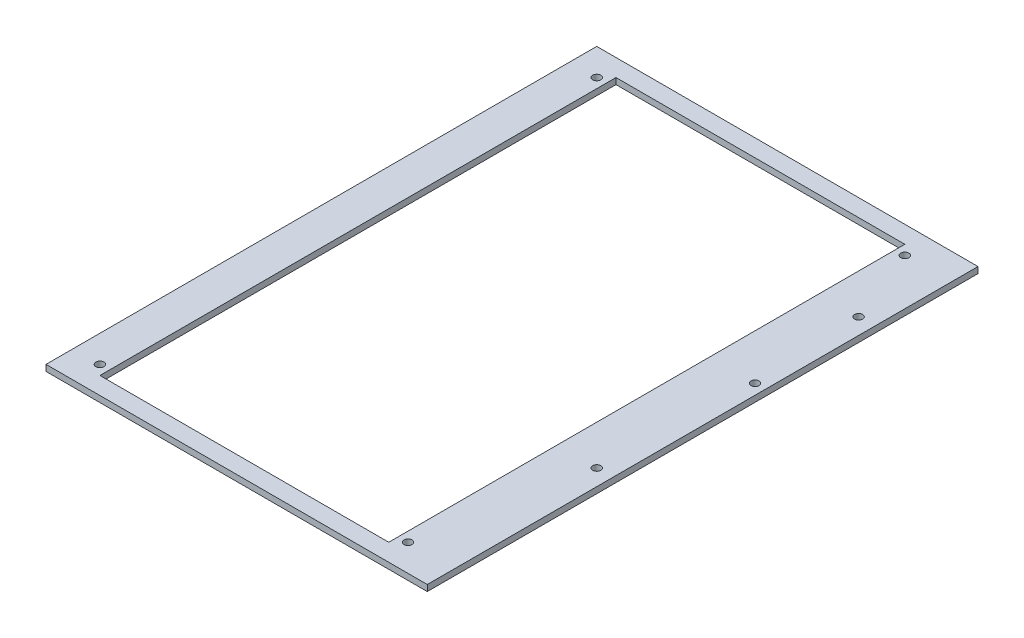
SolidWorks part; units mm, degrees
ref_plane "前视基准面" through (0, 0, 0) normal (0, 0, 1) x (1, 0, 0)
ref_plane "上视基准面" through (0, 0, 0) normal (0, 1, 0) x (1, 0, 0)
ref_plane "右视基准面" through (0, 0, 0) normal (1, 0, 0) x (0, 0, -1)
sketch "草图1" plane through (0, 0, 0) normal (0, 1, 0) x (1, 0, 0)
  line L1 (0, 0) -> (99, 0)
  line L2 (0, 0) -> (0, -99)
  line L3 (0, -99) -> (99, -99)
  line L4 (99, 0) -> (99, -99)
  line L5 (21.8, -26.8) -> (94.8, -26.8) construction
  line L6 (21.8, -26.8) -> (21.8, -94.8) construction
  line L7 (21.8, -94.8) -> (94.8, -94.8) construction
  line L8 (94.8, -26.8) -> (94.8, -94.8) construction
  line L9 (0, -99) -> (99, -99)
  line L10 (0, -99) -> (0, -143)
  line L11 (0, -143) -> (99, -143)
  line L12 (99, -99) -> (99, -143)
  line L13 (5, -5) -> (89, -5) construction
  line L14 (5, -5) -> (5, -138) construction
  line L15 (5, -138) -> (89, -138) construction
  line L16 (89, -5) -> (89, -138) construction
  line L17 (7, -7) -> (87, -7) construction
  line L18 (7, -7) -> (7, -136) construction
  line L19 (7, -136) -> (87, -136) construction
  line L20 (87, -7) -> (87, -136) construction
  line L21 (9.5, -4.5) -> (84.5, -4.5)
  line L22 (9.5, -4.5) -> (9.5, -138.5)
  line L23 (9.5, -138.5) -> (84.5, -138.5)
  line L24 (84.5, -4.5) -> (84.5, -138.5)
  circle A0 centre (21.8, -26.8) radius 1.05
  circle A1 centre (94.8, -26.8) radius 1.05
  circle A2 centre (21.8, -94.8) radius 1.05
  circle A3 centre (94.8, -94.8) radius 1.05
  circle A4 centre (8.7, -65.7) radius 1.05 construction
  circle A5 centre (81.9, -4.6) radius 1.05 construction
  circle A6 centre (96.3, -55.2) radius 1.05
  circle A7 centre (20, -12) radius 1.05
  circle A8 centre (71.4, -77.5) radius 1.05
  circle A9 centre (7, -7) radius 1.05
  circle A10 centre (87, -7) radius 1.05
  circle A11 centre (7, -136) radius 1.05
  circle A12 centre (87, -136) radius 1.05
  dimension "D7" = 2.1
  dimension "D8" = 2.1
  dimension "D9" = 2.1
  dimension "D10" = 2.1
  dimension "D21" = 2.1
  dimension "D22" = 2.1
  dimension "D23" = 2.1
  dimension "D24" = 2.1
  dimension "D25" = 2.1
  dimension "D33" = 2.1
  dimension "D34" = 2.1
  dimension "D35" = 2.1
  dimension "D36" = 2.1
  dimension "D39" = 4.5
  dimension "D1" = 99
  dimension "D2" = 99
  dimension "D3" = 21.8
  dimension "D4" = 4.2
  dimension "D5" = 68
  dimension "D6" = 73
  dimension "D11" = 8.7
  dimension "D12" = 33.3
  dimension "D13" = 81.9
  dimension "D14" = 94.4
  dimension "D15" = 96.3
  dimension "D16" = 43.8
  dimension "D17" = 20
  dimension "D18" = 87
  dimension "D19" = 71.4
  dimension "D20" = 21.5
  dimension "D26" = 143
  dimension "D27" = 2
  dimension "D28" = 2
  dimension "D29" = 2
  dimension "D30" = 2
  dimension "D31" = 84
  dimension "D32" = 133
  dimension "D37" = 5
  dimension "D38" = 5
  dimension "D40" = 4.5
  dimension "D41" = 0.5
  dimension "D42" = 0.5
extrude "凸台-拉伸1" add sketch "草图1" along normal blind 1.6 contours L4 L1 L2 L3 A10 A9 A8 A7 A6 A5 A4 A3 A2 A1 A0 | L12 L3 L10 L11 A12 A11
